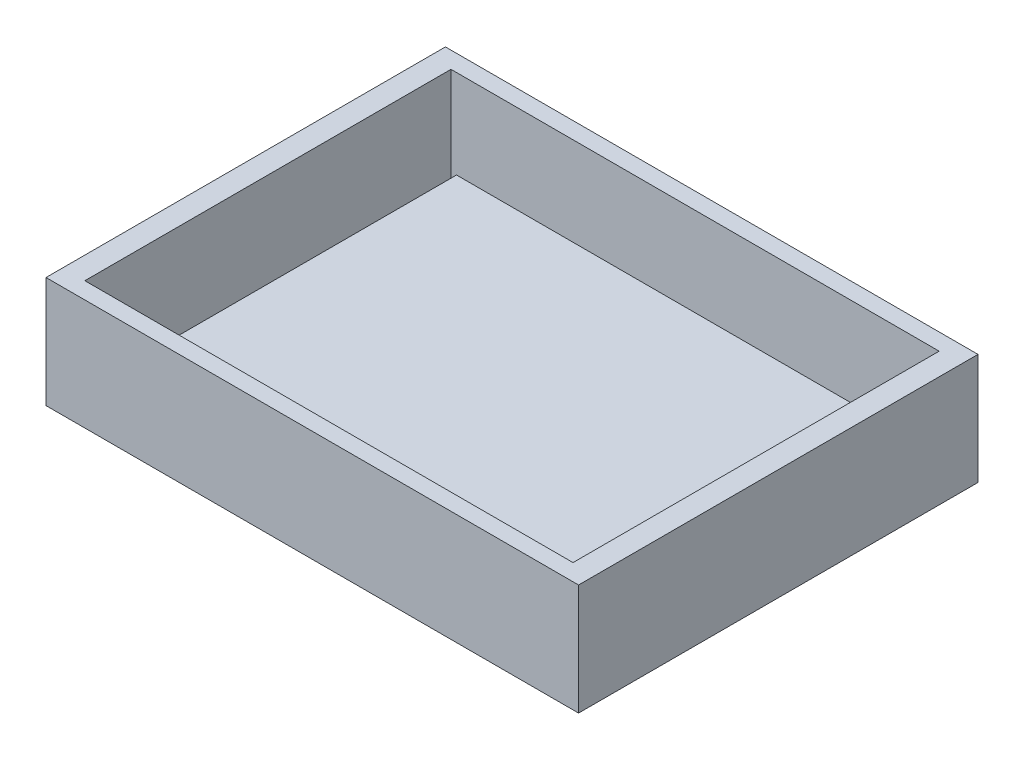
SolidWorks part; units mm, degrees
ref_plane "前视基准面" through (0, 0, 0) normal (0, 0, 1) x (1, 0, 0)
ref_plane "上视基准面" through (0, 0, 0) normal (0, 1, 0) x (1, 0, 0)
ref_plane "右视基准面" through (0, 0, 0) normal (1, 0, 0) x (0, 0, -1)
sketch "草图1" plane through (0, 0, 0) normal (0, 1, 0) x (1, 0, 0)
  line L1 (-34.1667, 34.4444) -> (45.8333, 34.4444)
  line L2 (-34.1667, 34.4444) -> (-34.1667, -25.5556)
  line L3 (-34.1667, -25.5556) -> (45.8333, -25.5556)
  line L4 (45.8333, 34.4444) -> (45.8333, -25.5556)
  dimension "D1" = 80
  dimension "D2" = 60
extrude "凸台-拉伸1" add sketch "草图1" along normal blind 5
sketch "草图2" plane through (0, 0, 0) normal (0, -1, 0) x (1, 0, 0)
  line L0 (-34.1667, 25.5556) -> (45.8333, 25.5556) construction
  line L1 (-42.1667, 33.5556) -> (53.8333, 33.5556)
  line L2 (-42.1667, 33.5556) -> (-42.1667, -38.4444)
  line L3 (-42.1667, -38.4444) -> (53.8333, -38.4444)
  line L4 (53.8333, 33.5556) -> (53.8333, -38.4444)
  line L5 (-34.1667, -34.4444) -> (-34.1667, 25.5556) construction
  dimension "D1" = 96
  dimension "D2" = 72
  dimension "D3" = 8
  dimension "D4" = 8
extrude "凸台-拉伸2" add sketch "草图2" against normal blind 20 contours L3 L4 L1 L2
sketch "草图3" plane through (0, 20, 0) normal (0, 1, 0) x (1, 0, 0)
  line L0 (-42.1667, 38.4444) -> (53.8333, 38.4444) construction
  line L1 (-38.1667, 35.4444) -> (49.8333, 35.4444)
  line L2 (-38.1667, 35.4444) -> (-38.1667, -30.5556)
  line L3 (-38.1667, -30.5556) -> (49.8333, -30.5556)
  line L4 (49.8333, 35.4444) -> (49.8333, -30.5556)
  line L5 (-42.1667, -33.5556) -> (-42.1667, 38.4444) construction
  dimension "D1" = 88
  dimension "D2" = 66
  dimension "D3" = 3
  dimension "D4" = 4
extrude "切除-拉伸1" cut sketch "草图3" against normal blind 18
sketch "草图5" plane through (0, 2, 0) normal (0, 1, 0) x (1, 0, 0)
  line L0 (49.8333, 35.4444) -> (-38.1667, 35.4444) construction
  line L1 (-34.1667, 32.4444) -> (45.8333, 32.4444)
  line L2 (-34.1667, 32.4444) -> (-34.1667, -27.5556)
  line L3 (-34.1667, -27.5556) -> (45.8333, -27.5556)
  line L4 (45.8333, 32.4444) -> (45.8333, -27.5556)
  line L5 (-38.1667, 35.4444) -> (-38.1667, -30.5556) construction
  dimension "D1" = 80
  dimension "D2" = 60
  dimension "D3" = 3
  dimension "D4" = 4
extrude "凸台-拉伸3" add sketch "草图5" along normal blind 5
